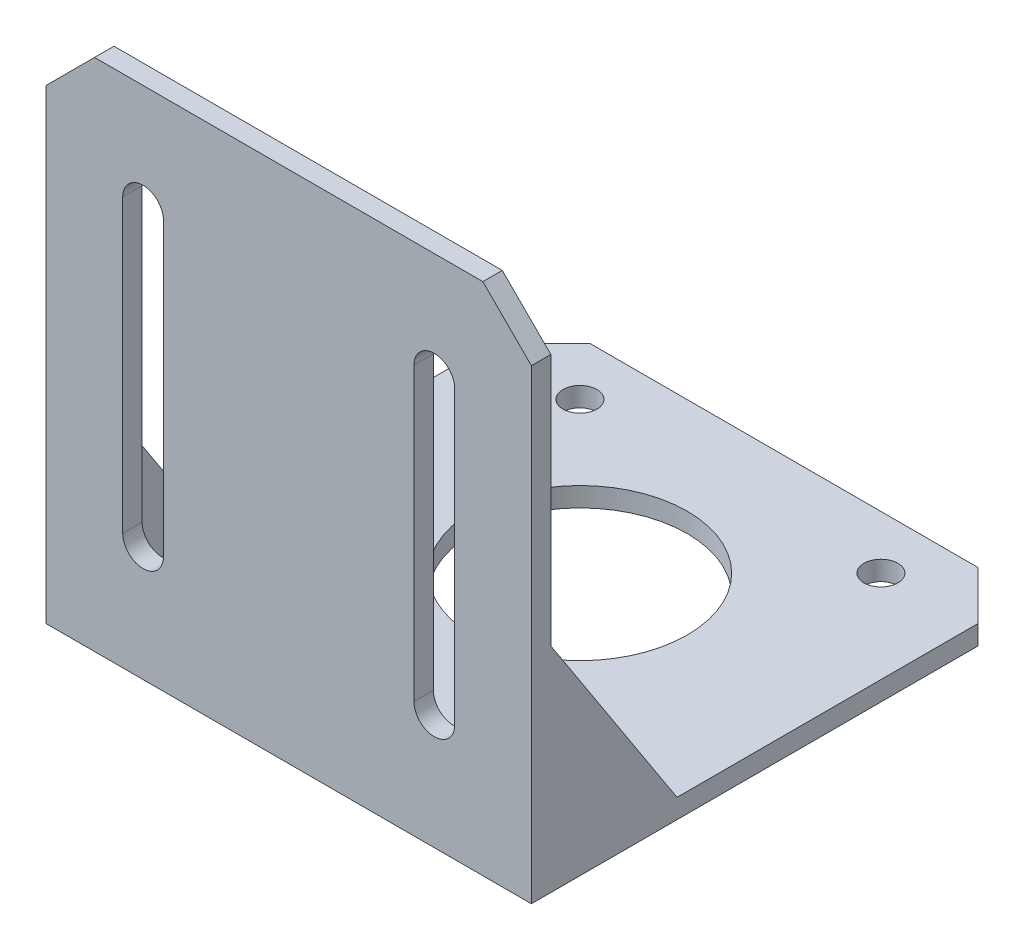
SolidWorks part; units mm, degrees
material "可锻铸铁"
ref_plane "前视基准面" through (0, 0, 0) normal (0, 0, 1) x (1, 0, 0)
ref_plane "上视基准面" through (0, 0, 0) normal (0, 1, 0) x (1, 0, 0)
ref_plane "右视基准面" through (0, 0, 0) normal (1, 0, 0) x (0, 0, -1)
sketch "草图1" plane through (0, 0, 0) normal (0, 1, 0) x (1, 0, 0)
  line L0 (0, 0) -> (0, 21) construction
  line L1 (-25, -28) -> (25, -28)
  line L2 (-25, -28) -> (-25, 21)
  line L3 (-25, 21) -> (25, 21)
  line L4 (25, -28) -> (25, 21)
  line L7 (0, 0) -> (25.0815, 0) construction
  circle A0 centre (0, 0) radius 11.05
  circle A1 centre (15.5, 15.5) radius 1.75
  circle A2 centre (15.5, -15.5) radius 1.75
  circle A3 centre (-15.5, -15.5) radius 1.75
  circle A4 centre (-15.5, 15.5) radius 1.75
  dimension "D1" = 22.1
  dimension "D4" = 3.5
  dimension "D5" = 31
  dimension "D6" = 31
  dimension "D3" = 21
  dimension "D2" = 50
  dimension "D7" = 49
extrude "凸台-拉伸1" add sketch "草图1" along normal blind 2
chamfer "倒角1" distance 5 angle 45 2 edges at (25, 1, -21) (-25, 1, -21)
sketch "草图3" plane through (0, 0, 0) normal (0, 1, 0) x (1, 0, 0)
  line L1 (-25, -28) -> (25, -28)
  line L2 (-25, -28) -> (-25, -30)
  line L3 (-25, -30) -> (25, -30)
  line L4 (25, -28) -> (25, -30)
  line L5 (-25, -28) -> (25, -30) construction
  line L6 (-25, -30) -> (25, -28) construction
  point P4 (0, -29)
  dimension "D1" = 2
extrude "凸台-拉伸2" add sketch "草图3" along normal blind 53
chamfer "倒角2" distance 5 angle 45 1 edges at (-25, 53, 29)
chamfer "倒角3" distance 5 angle 45 1 edges at (25, 53, 29)
sketch "草图4" plane through (0, 0, 28) normal (0, 0, -1) x (-1, 0, 0)
  line L0 (0, 53) -> (0, -10.599)
  line L1 (-20, 53) -> (20, 53) construction
  line L2 (-15, 42) -> (-15, 12) construction
  line L3 (-12.9, 42) -> (-12.9, 12)
  line L4 (-17.1, 42) -> (-17.1, 12)
  line L5 (15, 42) -> (15, 12) construction
  line L6 (12.9, 42) -> (12.9, 12)
  line L7 (17.1, 42) -> (17.1, 12)
  arc A0 (-12.9, 42) -> (-17.1, 42) centre (-15, 42) ccw
  arc A1 (-17.1, 12) -> (-12.9, 12) centre (-15, 12) ccw
  arc A2 (12.9, 42) -> (17.1, 42) centre (15, 42) cw
  arc A3 (17.1, 12) -> (12.9, 12) centre (15, 12) cw
  point P7 (-15, 27)
  point P14 (15, 27)
  dimension "D1" = 2.1
  dimension "D2" = 15
  dimension "D3" = 11
  dimension "D4" = 30
extrude "切除-拉伸1" cut sketch "草图4" against normal through all both and the other way through all contours L4 A1 L3 A0 | A3 L7 A2 L6
sketch "草图5" plane through (25, 0, 0) normal (1, 0, 0) x (0, 0, -1)
  line L0 (-28, 22) -> (-15, 2)
  line L1 (-28, 48) -> (-28, 2) construction
  line L2 (-28, 2) -> (16, 2) construction
  dimension "D1" = 20
  dimension "D2" = 13
rib "筋1" sketch "草图5" sketch "草图5" thickness 2 extrusion direction parallel to sketch draft on no parameters "D1"=2
mirror "镜向1" about plane through (0, 0, 0) normal (1, 0, 0) of "筋1"
fillet "圆角1" radius 2 1 edges at (0, 2, 28)
